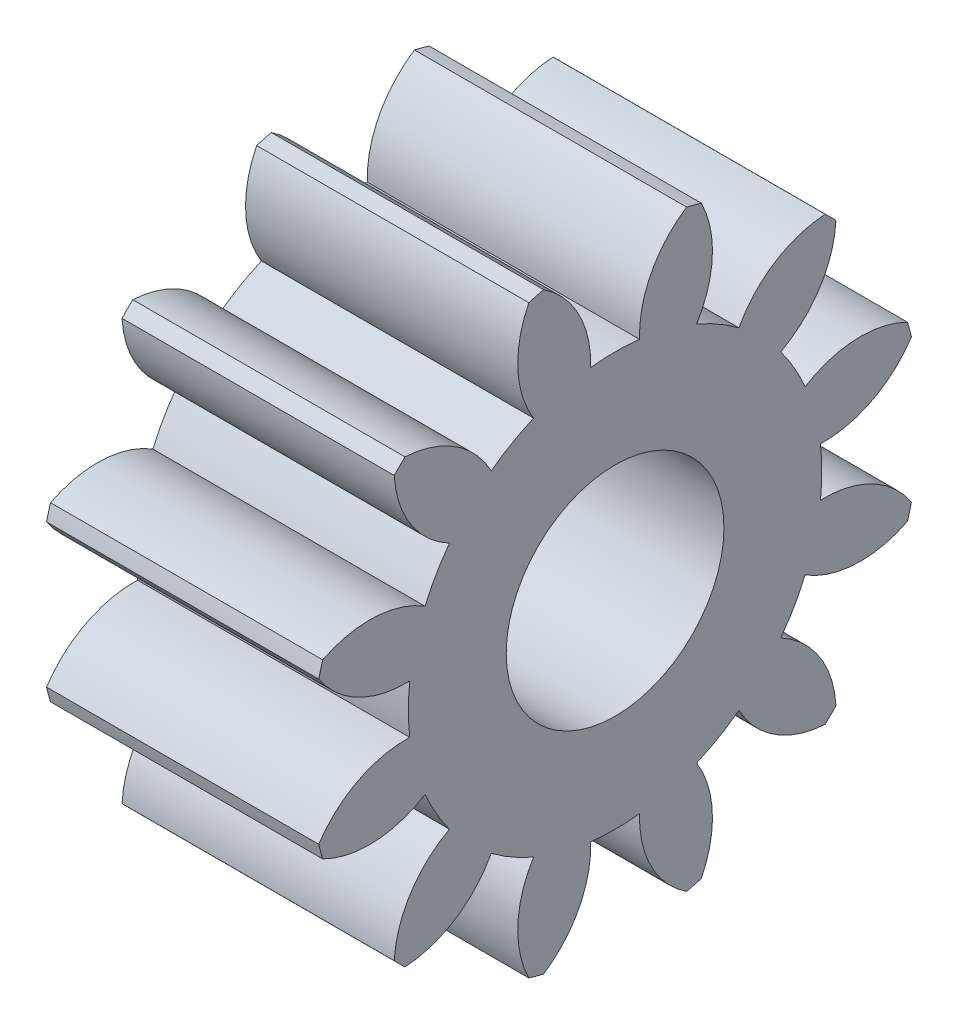
SolidWorks part; units mm, degrees
ref_plane "Plane1" through (0, 0, 0) normal (0, 0, 1) x (1, 0, 0)
ref_plane "Plane2" through (0, 0, 0) normal (0, 1, 0) x (1, 0, 0)
ref_plane "Plane3" through (0, 0, 0) normal (1, 0, 0) x (0, 0, -1)
sketch "HoldingSke" plane through (0, 0, 0) normal (0, 1, 0) x (1, 0, 0)
  line L0 (0, 0) -> (1.2227, -0.2599)
  line L1 (-15, 0) -> (100, 0) construction
  line L2 (0, 0) -> (-2.1039, 2.3779)
  line L3 (0, 0) -> (-11.863, 4.5341)
  line L4 (0, 0) -> (8.4473, 1.7955)
  line L5 (0, 0) -> (-46.8476, -17.4728)
  line L6 (0, 0) -> (-4.1448, -2.7965)
  line L7 (-2.1039, 2.3779) -> (8.6586, 51.2059)
  line L8 (-76.2, 54.61) -> (-75.5, 54.61)
  line L9 (-71.009, 38.7566) -> (-53.1078, 45.2721)
  line L10 (-76.2, 71.12) -> (104.1128, 71.12)
  line L11 (0, 0) -> (-5, 0)
  line L12 (-76.2, 101.6) -> (-76.17, 101.6)
  line L13 (24.9733, 27.94) -> (52.9518, 28.4284)
  line L14 (24.9733, 27.94) -> (24.9743, 27.94)
  line L15 (24.9733, 27.94) -> (100.4006, 29.5858)
  line L16 (-63.627, -0.8) -> (-12.827, -0.8)
  circle A0 centre (0, 0) radius 2
  circle A1 centre (0, 0) radius 3.799
  circle A2 centre (0, 0) radius 37.5
  circle A3 centre (0, 0) radius 2
  dimension "MHD" = 7.598
  dimension "Hub_dia" = 75
  dimension "Bore" = 4
  dimension "MBD" = 4
  dimension "Num_teeth" = 12
  dimension "Pitch" = 1.25
  dimension "Overall_len" = 50
  dimension "Show_teeth" = 12
  dimension "Thickness" = 5
  dimension "OAL" = 50.0001
  dimension "T_dim" = 0.7
  dimension "Ap" = 20
  dimension "H" = 19.05
  dimension "Pitch_radius" = 180.3128
  dimension "Width" = 5
  dimension "Backlash" = 0.03
  dimension "Addendum_fac" = 1
  dimension "Dedendum_fac" = 1.25
  dimension "Clearance_fac" = 0.25
  dimension "Dedendum_add" = 0.001
  dimension "Module" = 0.8
sketch "BasProSke" plane through (0, 0, 0) normal (0, 1, 0) x (1, 0, 0)
  line L0 (-10, 0) -> (60, 0) construction
  line L1 (0, 0) -> (0, 5.6)
  line L2 (0, 0) -> (5, 0)
  line L3 (5, 0) -> (5, 5.6)
  line L4 (5, 5.6) -> (0, 5.6)
  dimension "Thickness" = 5
  dimension "Diameter" = 11.2
revolve "Base-Revolve" add sketch "BasProSke" angle 360 about L0
sketch "TooCutSke" plane through (0, 0, 0) normal (1, 0, 0) x (0, 0, -1)
  line L1 (0, 0) -> (0, 107) construction
  line L2 (0, 0) -> (-0.6789, 4.7517) construction
  line L3 (0, 0) -> (-2.4668, 9.2063) construction
  line L4 (-0.6789, 4.7517) -> (-1.2334, 4.6032) construction
  arc A0 (0.4492, 3.7723) -> (-0.4492, 3.7723) centre (0, 0) ccw
  arc A1 (1.3434, 5.4626) -> (-1.3434, 5.4626) centre (0, 0) ccw
  circle A2 centre (0, 0) radius 4.8 construction
  circle A3 centre (0, 0) radius 4.5105 construction
  arc A4 (-0.4492, 3.7723) -> (-1.3434, 5.4626) centre (-2.3681, 3.8389) ccw
  arc A5 (1.3434, 5.4626) -> (0.4492, 3.7723) centre (2.3681, 3.8389) ccw
  dimension "Root_dia" = 7.598
  dimension "Overcut_dia" = 11.2508
  dimension "Pitch_dia" = 9.6
  dimension "Base_dia" = 9.021
  dimension "Flank_rad" = 1.92
  dimension "Half_ang" = 15
  dimension "Half_CT" = 0.574
extrude "ToothCut" cut sketch "TooCutSke" along normal through all
fillet "Breaks" [suppressed] radius 0.016
fillet "RootFillets" [suppressed] radius 0.201
pattern_circular "TeethCuts" count 12 every 30 about axis through (-10, 0, 0) along (1, 0, 0) of "ToothCut", "RootFillets", "Breaks"
sketch "HubNeaOneSke" plane through (0, 0, 0) normal (-1, 0, 0) x (0, 0, 1)
  circle A0 centre (0, 0) radius 3.799
  dimension "Diameter" = 7.598
extrude "HubNearOne" [suppressed] add sketch "HubNeaOneSke" along normal blind 45.0001
sketch "HubNeaBotSke" plane through (0, 0, 0) normal (-1, 0, 0) x (0, 0, 1)
  circle A0 centre (0, 0) radius 3.799
  dimension "Diameter" = 7.598
extrude "HubNearBoth" [suppressed] add sketch "HubNeaBotSke" along normal blind 22.5
ref_plane "FarPln" through (5, 0, 0) normal (1, 0, 0) x (0, 0, -1)
sketch "HubFarSke" plane through (5, 0, 0) normal (1, 0, 0) x (0, 0, -1)
  circle A0 centre (0, 0) radius 3.799
  dimension "Diameter" = 7.598
extrude "HubFar" [suppressed] add sketch "HubFarSke" along normal blind 22.5
sketch "BorSke" plane through (0, 0, 0) normal (1, 0, 0) x (0, 0, -1)
  circle A0 centre (0, 0) radius 2
  dimension "Diameter" = 4
extrude "Bore" cut sketch "BorSke" along normal mid plane 100.0001
sketch "KeySke" plane through (0, 0, 0) normal (1, 0, 0) x (0, 0, -1)
  line L0 (-0.8, 0) -> (-0.8, 2.7)
  line L1 (-0.8, 2.7) -> (0.8, 2.7)
  line L2 (0.8, 2.7) -> (0.8, 0)
  line L3 (0, 0) -> (0, 34) construction
  line L4 (-0.8, 0) -> (0.8, 0)
  dimension "Offset" = 2.7
  dimension "Width" = 1.6
extrude "Keyway" [suppressed] cut sketch "KeySke" along normal mid plane 100.0001
pattern_circular "Keyway2" [suppressed] count 2 every 90 about axis through (-10, 0, 0) along (1, 0, 0)
equation "' \"Module@HoldingSke\" = 6.35"
equation "' \"Num_teeth@HoldingSke\" = 12"
equation "' \"Ap@HoldingSke\" =  20"
equation "' \"Ap@HoldingSke\" = 20"
equation "' \"Width@HoldingSke\" = 0.5 * 25.4"
equation "' \"Hub_dia@HoldingSke\"= 1 * 25.4"
equation "' \"Hub_dia@HoldingSke\" = 1 * 25.4"
equation "' \"Overall_len@HoldingSke\" = 1.0 * 25.4"
equation "' \"Bore@HoldingSke\" = 0.75 * 25.4"
equation "' \"T_dim@HoldingSke\" = 0.1 * 25.4"
equation "' \"Width@KeySke\" = 0.25 * 25.4"
equation "' \"Show_teeth@HoldingSke\" = 13"
equation "' \"Backlash@HoldingSke\" = 0.009 * 25.4"
equation "' \"Addendum_fac@HoldingSke\" = 1.0"
equation "' \"Dedendum_fac@HoldingSke\" = 1.25"
equation "' \"Dedendum_add@HoldingSke\" = 0.00005 * 25.4"
equation "' \"Clearance_fac@HoldingSke\" = 0.25"
equation "\"Pitch@HoldingSke\" = 1 / \"Module@HoldingSke\""
equation "\"Overcut_dia@TooCutSke\" = (\"Num_teeth@HoldingSke\" + 2 * \"Addendum_fac@HoldingSke\") / \"Pitch@HoldingSke\" + 0.002 * 25.4"
equation "\"Pitch_dia@TooCutSke\" = \"Num_teeth@HoldingSke\" / \"Pitch@HoldingSke\""
equation "\"Base_dia@TooCutSke\" = \"Num_teeth@HoldingSke\" / \"Pitch@HoldingSke\" * cos((\"Ap@HoldingSke\"  * 3.14159265 / 180))"
equation "\"Root_dia@TooCutSke\" = (\"Num_teeth@HoldingSke\" + 2) / \"Pitch@HoldingSke\" - 2 * (\"Addendum_fac@HoldingSke\" + \"Dedendum_fac@HoldingSke\") / \"Pitch@HoldingSke\" - \"Dedendum_add@HoldingSke\" * 2"
equation "\"Half_ang@TooCutSke\" = 180 / \"Num_teeth@HoldingSke\""
equation "\"Half_CT@TooCutSke\" = \"Num_teeth@HoldingSke\" / \"Pitch@HoldingSke\" * sin((3.14159265 / 2 / \"Num_teeth@HoldingSke\")) / 2 - 7 * \"Backlash@HoldingSke\" / 4"
equation "\"Flank_rad@TooCutSke\" = \"Num_teeth@HoldingSke\" / \"Pitch@HoldingSke\" / 5"
equation "\"Radius@RootFillets\" = \"Clearance_fac@HoldingSke\" / \"Pitch@HoldingSke\" + \"Dedendum_add@HoldingSke\""
equation "\"Break_rad@Breaks\" = 0.02 / \"Pitch@HoldingSke\""
equation "\"Thickness@HoldingSke\" = \"Width@HoldingSke\""
equation "\"OAL@HoldingSke\" = \"Thickness@HoldingSke\""
equation "\"MHD@HoldingSke\" = (\"Num_teeth@HoldingSke\" + 2) / \"Pitch@HoldingSke\" - 2 * (\"Addendum_fac@HoldingSke\" + \"Dedendum_fac@HoldingSke\")  / \"Pitch@HoldingSke\" - \"Dedendum_add@HoldingSke\" * 2"
equation "\"MBD@HoldingSke\" = (\"Num_teeth@HoldingSke\" + 2) / \"Pitch@HoldingSke\" - 2 * (\"Addendum_fac@HoldingSke\" + \"Dedendum_fac@HoldingSke\")  / \"Pitch@HoldingSke\" - \"Dedendum_add@HoldingSke\" * 2 - 0.002 * 25.4"
equation "\"MHD@HoldingSke\" = ((sgn( \"MHD@HoldingSke\" - \"Hub_dia@HoldingSke\" )-1)*( \"MHD@HoldingSke\" - \"Hub_dia@HoldingSke\" ))/-2+ \"Hub_dia@HoldingSke\""
equation "\"MBD@HoldingSke\" = ((sgn( \"MBD@HoldingSke\" - \"Bore@HoldingSke\" )-1)*( \"MBD@HoldingSke\" - \"Bore@HoldingSke\" ))/-2+ \"Bore@HoldingSke\""
equation "\"OAL@HoldingSke\" = ((sgn( \"OAL@HoldingSke\" - \"Overall_len@HoldingSke\" )+1)*( \"OAL@HoldingSke\" - \"Overall_len@HoldingSke\" ))/2 + \"Overall_len@HoldingSke\" + 0.000002 * 25.4"
equation "\"Num_teeth@TeethCuts\" = int( \"Show_teeth@HoldingSke\" ) + 1"
equation "\"Num_teeth@TeethCuts\" = ((sgn( \"Num_teeth@TeethCuts\" - \"Num_teeth@HoldingSke\" )-1)*( \"Num_teeth@TeethCuts\" - \"Num_teeth@HoldingSke\" ))/-2+ \"Num_teeth@HoldingSke\""
equation "\"Num_teeth@TeethCuts\" = ((sgn( \"Num_teeth@TeethCuts\" - 2.0)+1)*( \"Num_teeth@TeethCuts\" - 2.0))/2 +2.0"
equation "\"Angle@TeethCuts\" = 360.0 / \"Num_teeth@HoldingSke\""
equation "\"Diameter@BasProSke\" = (\"Num_teeth@HoldingSke\" + 2 * \"Addendum_fac@HoldingSke\") / \"Pitch@HoldingSke\""
equation "\"Thickness@BasProSke\"  = \"Thickness@HoldingSke\""
equation "' \"Fillet_rad@BasProSke\" =  \"Thickness@HoldingSke\" * 0.05"
equation "' \"Fillet_rad@BasProSke\" = \"Thickness@HoldingSke\" * 0.05"
equation "\"MHD@HoldingSke\" = ((sgn( \"MHD@HoldingSke\" - \"Root_dia@TooCutSke\" )-1)*( \"MHD@HoldingSke\" - \"Root_dia@TooCutSke\" ))/-2+ \"Root_dia@TooCutSke\""
equation "\"Diameter@HubNeaOneSke\" = \"MHD@HoldingSke\""
equation "\"Length@HubNearOne\" = \"OAL@HoldingSke\" - \"Thickness@BasProSke\""
equation "\"Diameter@HubNeaBotSke\" = \"MHD@HoldingSke\""
equation "\"Length@HubNearBoth\" = ( \"OAL@HoldingSke\" - \"Thickness@BasProSke\" ) / 2.0"
equation "\"Thickness@FarPln\" = \"Thickness@BasProSke\""
equation "\"Diameter@HubFarSke\" = \"MHD@HoldingSke\""
equation "\"Length@HubFar\" = ( \"OAL@HoldingSke\" - \"Thickness@BasProSke\" ) / 2.0"
equation "\"Diameter@BorSke\" = \"MBD@HoldingSke\""
equation "\"D1@Bore\" = \"OAL@HoldingSke\" * 2.0"
equation "\"D1@Keyway\" = \"OAL@HoldingSke\" * 2.0"
equation "\"Offset@KeySke\" = \"T_dim@HoldingSke\" + \"MBD@HoldingSke\" / 2.0"
